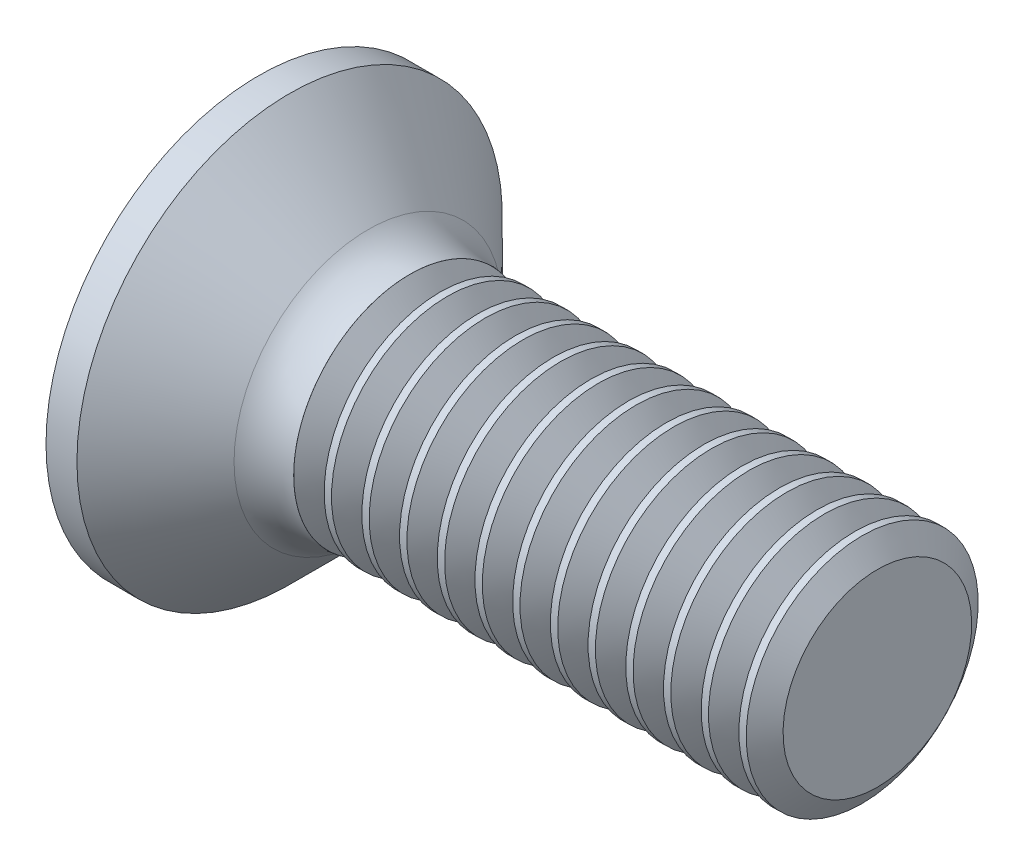
SolidWorks part; units mm, degrees
ref_plane "Plane1" through (0, 0, 0) normal (0, 0, 1) x (1, 0, 0)
ref_plane "Plane2" through (0, 0, 0) normal (0, 1, 0) x (1, 0, 0)
ref_plane "Plane3" through (0, 0, 0) normal (1, 0, 0) x (0, 0, -1)
other "Configuration Table"
sketch "BodySke" plane through (0, 0, 0) normal (0, 0, 1) x (1, 0, 0)
  line L0 (0, 0) -> (8.7, 0)
  line L1 (8.7, 0) -> (8.7, 1.5)
  line L2 (8.7, 1.5) -> (2.35, 1.5)
  line L3 (1.1, -2.75) -> (2.35, -1.5) construction
  line L4 (-15.875, 0) -> (82.55, 0) construction
  line L5 (1.1, 2.75) -> (2.35, 1.5)
  line L6 (2.85, 4.675) -> (2.85, -11.2) construction
  line L7 (0.7, 2.7793) -> (0.7, -13.0957) construction
  line L8 (1.1, 2.75) -> (0.7, 2.75)
  arc A0 (0, 0) -> (0.7, 2.75) centre (5.7518, 0) cw
  dimension "Head_ang" = 90
  dimension "Diameter" = 3
  dimension "Advance" = 0.5
  dimension "Thread_nom" = 8
  dimension "Oval_ht" = 0.7
  dimension "Side_ht" = 1.65
  dimension "Head_dia" = 5.5
  dimension "Length" = 8
revolve "Base-Revolve" add sketch "BodySke" angle 360 about L4
cosmetic thread "ThreadCosmetic" [suppressed] parameters "Thread_length"=5.85, "Thread_minor"=2.439
fillet "Fillet1" radius 0.8 1 edges at (2.35, 0, 1.5)
sketch "Sketch3" plane through (0, 0, 0) normal (1, 0, 0) x (0, 0, -1)
  line L0 (0.37, -1.55) -> (-0.37, -1.55)
  line L1 (0.37, -1.55) -> (0.37, 1.55)
  line L2 (-0.37, 1.55) -> (0.37, 1.55)
  line L3 (-0.37, 1.55) -> (-0.37, -1.55)
  dimension "Cross_width" = 0.74
  dimension "D1" = 0.37
  dimension "Cross_dia" = 3.1
  dimension "D2" = 1.55
ref_plane "Plane4" through (2.08, 0, 0) normal (1, 0, 0) x (0, 0, -1)
sketch "Sketch4" plane through (2.08, 0, 0) normal (1, 0, 0) x (0, 0, -1)
  line L0 (0.37, -0.513) -> (-0.37, -0.513)
  line L1 (0.37, -0.513) -> (0.37, 0.513)
  line L2 (-0.37, 0.513) -> (0.37, 0.513)
  line L3 (-0.37, 0.513) -> (-0.37, -0.513)
  dimension "D1" = 0.74
  dimension "D2" = 1.0259
  dimension "D3" = 0.37
  dimension "D4" = 0.513
loft "Recess" cut profiles "Sketch3", "Sketch4"
pattern_circular "RecPat" count 2 every 90 about axis through (0, 0, 0) along (1, 0, 0) of "Recess"
sketch "RecCorSke" plane through (0, 0, 0) normal (0, 0, 1) x (1, 0, 0)
  line L0 (-3.175, 0) -> (15.875, 0) construction
  line L2 (0, 0) -> (0, 0.7014)
  line L3 (0, 0.7014) -> (2.08, 0.556)
  line L4 (2.08, 0.556) -> (2.2607, 0)
  line L5 (2.2607, 0) -> (0, 0)
  dimension "Diameter" = 1.112
  dimension "Depth" = 2.08
  dimension "Draft_angle" = 4
  dimension "Bottom_angle" = 18
revolve "RecessCore" cut sketch "RecCorSke" angle 360 about L0
sketch "ThdSchSke" plane through (0, 0, 0) normal (0, 0, 1) x (1, 0, 0)
  line L0 (2.85, -1.2195) -> (2.6536, -1.5)
  line L1 (2.85, -1.2195) -> (3.0464, -1.5)
  line L2 (3.0464, -1.5) -> (3.0464, -1.875)
  line L3 (-3.175, 0) -> (5.1513, 0) construction
  line L5 (3.0464, -1.875) -> (2.6536, -1.875)
  line L6 (2.6536, -1.875) -> (2.6536, -1.5)
  dimension "Diameter" = 3
  dimension "SideAngle" = 55
  dimension "VeeAngle" = 70
  dimension "Thread_minor" = 2.439
  dimension "Overcut" = 3.75
  dimension "Start" = 2.85
revolve "ThreadSchematic" cut sketch "ThdSchSke" angle 360 about L3
pattern_linear "ThdSchPat" count 13 spacing 0.4875 along (1, 0, 0) of "ThreadSchematic"
equation "\"D1@Sketch3\" = \"Cross_width@Sketch3\" / 2"
equation "\"D2@Sketch3\" = \"Cross_dia@Sketch3\" / 2"
equation "\"Depth@RecCorSke\" = \"Cross_depth@Plane4\""
equation "\"D1@Sketch4\" = \"Cross_width@Sketch3\""
equation "\"D2@Sketch4\" = \"Cross_dia@Sketch3\" - 2.0 * \"Cross_depth@Plane4\" * tan(26.5  * 0.017453292)"
equation "\"D3@Sketch4\" = \"D1@Sketch4\" / 2"
equation "\"D4@Sketch4\" = \"D2@Sketch4\" / 2"
equation "\"Thread_length@ThreadCosmetic\" = ((sgn( (\"Length@BodySke\" - \"Advance@BodySke\" - \"Side_ht@BodySke\" ) - \"Thread_nom@BodySke\" )-1)*( (\"Length@BodySke\" - \"Advance@BodySke\" - \"Side_ht@BodySke\" ) - \"Thread_nom@BodySke\" ))/-2+ \"Thread_nom@BodySke\""
equation "\"Thread_minor@ThdSchSke\" = \"Thread_minor@ThreadCosmetic\""
equation "\"Diameter@ThdSchSke\" = \"Diameter@BodySke\""
equation "\"Overcut@ThdSchSke\" = \"Diameter@BodySke\" * 1.25"
equation "\"Start@ThdSchSke\" = \"Oval_ht@BodySke\" + \"Length@BodySke\" - \"Thread_length@ThreadCosmetic\"  '---Countersunk---"
equation "\"Num_threads@ThdSchPat\" = int( \"Thread_length@ThreadCosmetic\" / \"Advance@BodySke\" + 0.999 )  + 1"
equation "\"Advance@ThdSchPat\" = \"Thread_length@ThreadCosmetic\" /  (\"Num_threads@ThdSchPat\" - 1) 'relax it"
